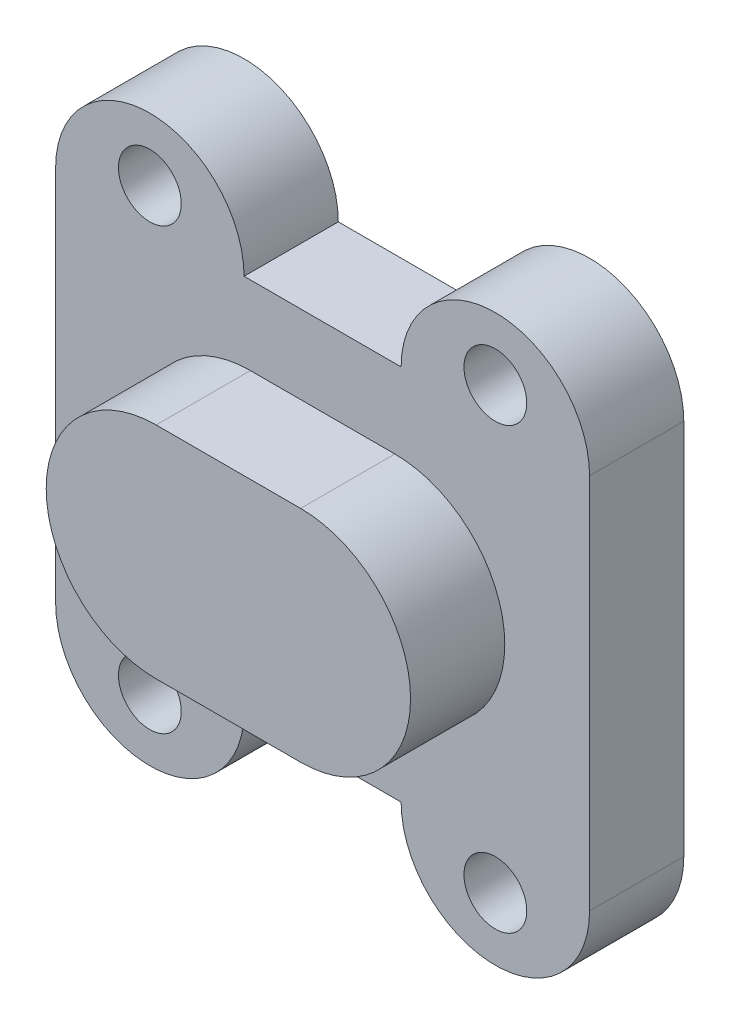
SolidWorks part; units mm, degrees
ref_plane "前视基准面" through (0, 0, 0) normal (0, 0, 1) x (1, 0, 0)
ref_plane "上视基准面" through (0, 0, 0) normal (0, 1, 0) x (1, 0, 0)
ref_plane "右视基准面" through (0, 0, 0) normal (1, 0, 0) x (0, 0, -1)
other "Configuration Table"
sketch "草图1" plane through (0, 0, 0) normal (0, 0, 1) x (1, 0, 0)
  line L1 (0, 0) -> (11, 0) construction
  line L2 (0, 0) -> (0, -14) construction
  line L3 (0, -14) -> (11, -14) construction
  line L4 (11, 0) -> (11, -14) construction
  line L5 (3, -13) -> (8, -13)
  line L6 (-3, -1) -> (-3, -13)
  line L7 (14, -1) -> (14, -13)
  line L8 (3, -1) -> (8, -1)
  circle A1 centre (11, -14) radius 1
  circle A2 centre (0, 0) radius 1
  circle A3 centre (11, 0) radius 1
  circle A4 centre (0, -14) radius 1
  arc A7 (-3, -13) -> (3, -13) centre (0, -13) ccw
  arc A8 (8, -13) -> (14, -13) centre (11, -13) ccw
  arc A9 (14, -1) -> (8, -1) centre (11, -1) ccw
  arc A10 (3, -1) -> (-3, -1) centre (0, -1) ccw
  point P15 (3, -13)
  point P23 (3, -1.1522)
  dimension "D3" = 6
  dimension "D4" = 2
  dimension "D5" = 2
  dimension "D6" = 2
  dimension "D7" = 2
  dimension "D8" = 6
  dimension "D9" = 6
  dimension "D10" = 6
  dimension "D11" = 1
  dimension "D1" = 14
  dimension "D2" = 11
extrude "凸台-拉伸1" add sketch "草图1" along normal blind 3
sketch "草图2" plane through (0, 0, 3) normal (0, 0, 1) x (1, 0, 0)
  line L0 (-3, -7) -> (14, -7) construction
  line L1 (-3, -1) -> (-3, -13) construction
  line L2 (14, -13) -> (14, -1) construction
  line L3 (5.5, -1) -> (5.5, -13) construction
  line L4 (8, -1) -> (3, -1) construction
  line L5 (3, -13) -> (8, -13) construction
  line L6 (3.2, -7) -> (7.8, -7) construction
  line L7 (3.2, -3.5) -> (7.8, -3.5)
  line L8 (3.2, -10.5) -> (7.8, -10.5)
  arc A0 (3.2, -3.5) -> (3.2, -10.5) centre (3.2, -7) ccw
  arc A1 (7.8, -10.5) -> (7.8, -3.5) centre (7.8, -7) ccw
  point P14 (5.5, -7)
  point P19 (4.7449, -7)
  point P20 (5.5, -7)
  point P21 (0, 0)
  point P22 (6.4192, -7)
  dimension "D1" = 7
  dimension "D2" = 4.6
extrude "凸台-拉伸2" add sketch "草图2" along normal blind 3
